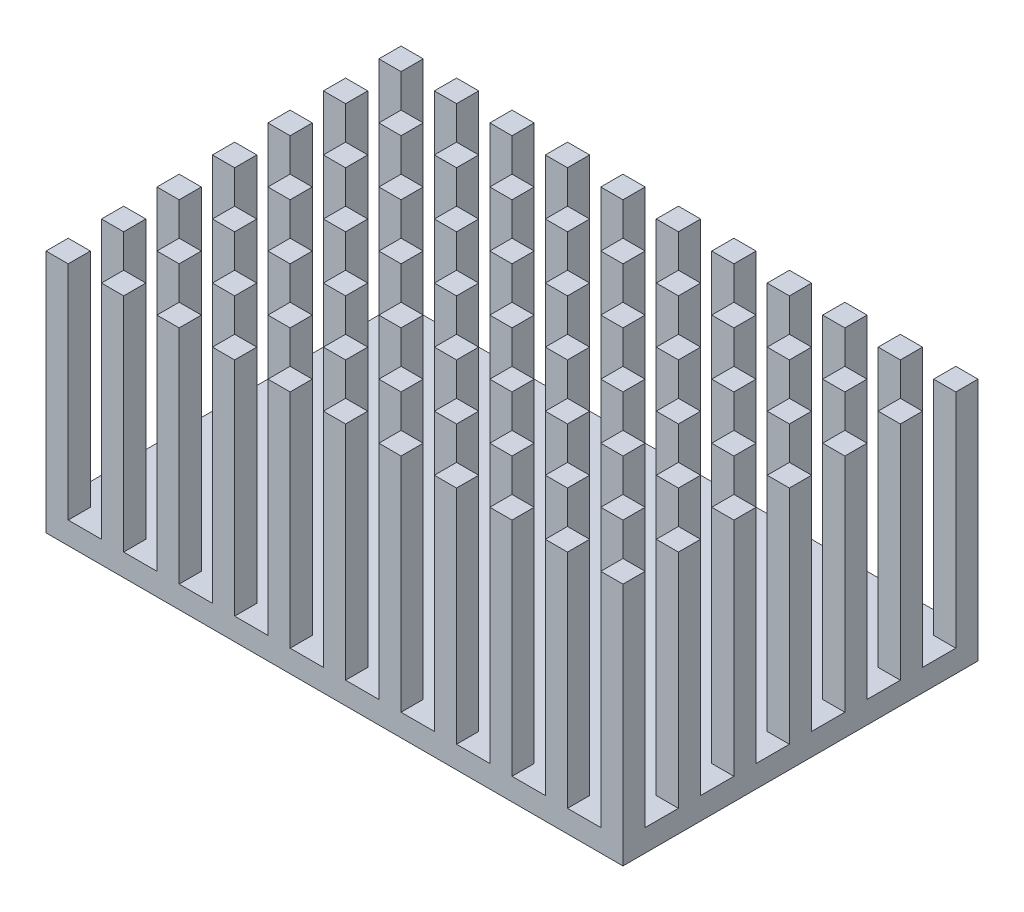
SolidWorks part; units mm, degrees
ref_plane "Front Plane" through (0, 0, 0) normal (0, 0, 1) x (1, 0, 0)
ref_plane "Top Plane" through (0, 0, 0) normal (0, 1, 0) x (1, 0, 0)
ref_plane "Right Plane" through (0, 0, 0) normal (1, 0, 0) x (0, 0, -1)
sketch "Sketch1" plane through (0, 0, 0) normal (0, 1, 0) x (1, 0, 0)
  line L1 (-26, 16) -> (26, 16)
  line L2 (-26, 16) -> (-26, -16)
  line L3 (-26, -16) -> (26, -16)
  line L4 (26, 16) -> (26, -16)
  line L5 (-26, 16) -> (26, -16) construction
  line L6 (-26, -16) -> (26, 16) construction
  point P0 (0, 0)
  dimension "D1" = 52
  dimension "D2" = 32
extrude "Boss-Extrude1" add sketch "Sketch1" along normal blind 2
sketch "Sketch2" plane through (0, 2, 0) normal (0, 1, 0) x (1, 0, 0)
  line L0 (-21, 16) -> (-19, 16)
  line L1 (-26, 16) -> (-24, 16)
  line L2 (-26, 16) -> (-26, 14)
  line L3 (-26, 14) -> (-24, 14)
  line L4 (-24, 16) -> (-24, 14)
  line L5 (-21, 16) -> (-21, 14)
  line L6 (-21, 14) -> (-19, 14)
  line L7 (-19, 16) -> (-19, 14)
  line L8 (-16, 16) -> (-14, 16)
  line L9 (-16, 16) -> (-16, 14)
  line L10 (-16, 14) -> (-14, 14)
  line L11 (-14, 16) -> (-14, 14)
  line L12 (-11, 16) -> (-9, 16)
  line L13 (-11, 16) -> (-11, 14)
  line L14 (-11, 14) -> (-9, 14)
  line L15 (-9, 16) -> (-9, 14)
  line L16 (-6, 16) -> (-4, 16)
  line L17 (-6, 16) -> (-6, 14)
  line L18 (-6, 14) -> (-4, 14)
  line L19 (-4, 16) -> (-4, 14)
  line L20 (-1, 16) -> (1, 16)
  line L21 (-1, 16) -> (-1, 14)
  line L22 (-1, 14) -> (1, 14)
  line L23 (1, 16) -> (1, 14)
  line L24 (4, 16) -> (6, 16)
  line L25 (4, 16) -> (4, 14)
  line L26 (4, 14) -> (6, 14)
  line L27 (6, 16) -> (6, 14)
  line L28 (9, 16) -> (11, 16)
  line L29 (9, 16) -> (9, 14)
  line L30 (9, 14) -> (11, 14)
  line L31 (11, 16) -> (11, 14)
  line L32 (14, 16) -> (16, 16)
  line L33 (14, 16) -> (14, 14)
  line L34 (14, 14) -> (16, 14)
  line L35 (16, 16) -> (16, 14)
  line L36 (19, 16) -> (21, 16)
  line L37 (19, 16) -> (19, 14)
  line L38 (19, 14) -> (21, 14)
  line L39 (21, 16) -> (21, 14)
  line L40 (24, 16) -> (26, 16)
  line L41 (24, 16) -> (24, 14)
  line L42 (24, 14) -> (26, 14)
  line L43 (26, 16) -> (26, 14)
  line L44 (-21, 11) -> (-19, 11)
  line L45 (-21, 11) -> (-21, 9)
  line L46 (-21, 9) -> (-19, 9)
  line L47 (-19, 11) -> (-19, 9)
  line L48 (-16, 11) -> (-14, 11)
  line L49 (-16, 11) -> (-16, 9)
  line L50 (-16, 9) -> (-14, 9)
  line L51 (-14, 11) -> (-14, 9)
  line L52 (-11, 11) -> (-9, 11)
  line L53 (-11, 11) -> (-11, 9)
  line L54 (-11, 9) -> (-9, 9)
  line L55 (-9, 11) -> (-9, 9)
  line L56 (-6, 11) -> (-4, 11)
  line L57 (-6, 11) -> (-6, 9)
  line L58 (-6, 9) -> (-4, 9)
  line L59 (-4, 11) -> (-4, 9)
  line L60 (-1, 11) -> (1, 11)
  line L61 (-1, 11) -> (-1, 9)
  line L62 (-1, 9) -> (1, 9)
  line L63 (1, 11) -> (1, 9)
  line L64 (4, 11) -> (6, 11)
  line L65 (4, 11) -> (4, 9)
  line L66 (4, 9) -> (6, 9)
  line L67 (6, 11) -> (6, 9)
  line L68 (9, 11) -> (11, 11)
  line L69 (9, 11) -> (9, 9)
  line L70 (9, 9) -> (11, 9)
  line L71 (11, 11) -> (11, 9)
  line L72 (14, 11) -> (16, 11)
  line L73 (14, 11) -> (14, 9)
  line L74 (14, 9) -> (16, 9)
  line L75 (16, 11) -> (16, 9)
  line L76 (19, 11) -> (21, 11)
  line L77 (19, 11) -> (19, 9)
  line L78 (19, 9) -> (21, 9)
  line L79 (21, 11) -> (21, 9)
  line L80 (24, 11) -> (26, 11)
  line L81 (24, 11) -> (24, 9)
  line L82 (24, 9) -> (26, 9)
  line L83 (26, 11) -> (26, 9)
  line L84 (-21, 6) -> (-19, 6)
  line L85 (-21, 6) -> (-21, 4)
  line L86 (-21, 4) -> (-19, 4)
  line L87 (-19, 6) -> (-19, 4)
  line L88 (-16, 6) -> (-14, 6)
  line L89 (-16, 6) -> (-16, 4)
  line L90 (-16, 4) -> (-14, 4)
  line L91 (-14, 6) -> (-14, 4)
  line L92 (-11, 6) -> (-9, 6)
  line L93 (-11, 6) -> (-11, 4)
  line L94 (-11, 4) -> (-9, 4)
  line L95 (-9, 6) -> (-9, 4)
  line L96 (-6, 6) -> (-4, 6)
  line L97 (-6, 6) -> (-6, 4)
  line L98 (-6, 4) -> (-4, 4)
  line L99 (-4, 6) -> (-4, 4)
  line L100 (-1, 6) -> (1, 6)
  line L101 (-1, 6) -> (-1, 4)
  line L102 (-1, 4) -> (1, 4)
  line L103 (1, 6) -> (1, 4)
  line L104 (4, 6) -> (6, 6)
  line L105 (4, 6) -> (4, 4)
  line L106 (4, 4) -> (6, 4)
  line L107 (6, 6) -> (6, 4)
  line L108 (9, 6) -> (11, 6)
  line L109 (9, 6) -> (9, 4)
  line L110 (9, 4) -> (11, 4)
  line L111 (11, 6) -> (11, 4)
  line L112 (14, 6) -> (16, 6)
  line L113 (14, 6) -> (14, 4)
  line L114 (14, 4) -> (16, 4)
  line L115 (16, 6) -> (16, 4)
  line L116 (19, 6) -> (21, 6)
  line L117 (19, 6) -> (19, 4)
  line L118 (19, 4) -> (21, 4)
  line L119 (21, 6) -> (21, 4)
  line L120 (24, 6) -> (26, 6)
  line L121 (24, 6) -> (24, 4)
  line L122 (24, 4) -> (26, 4)
  line L123 (26, 6) -> (26, 4)
  line L124 (-21, 1) -> (-19, 1)
  line L125 (-21, 1) -> (-21, -1)
  line L126 (-21, -1) -> (-19, -1)
  line L127 (-19, 1) -> (-19, -1)
  line L128 (-16, 1) -> (-14, 1)
  line L129 (-16, 1) -> (-16, -1)
  line L130 (-16, -1) -> (-14, -1)
  line L131 (-14, 1) -> (-14, -1)
  line L132 (-11, 1) -> (-9, 1)
  line L133 (-11, 1) -> (-11, -1)
  line L134 (-11, -1) -> (-9, -1)
  line L135 (-9, 1) -> (-9, -1)
  line L136 (-6, 1) -> (-4, 1)
  line L137 (-6, 1) -> (-6, -1)
  line L138 (-6, -1) -> (-4, -1)
  line L139 (-4, 1) -> (-4, -1)
  line L140 (-1, 1) -> (1, 1)
  line L141 (-1, 1) -> (-1, -1)
  line L142 (-1, -1) -> (1, -1)
  line L143 (1, 1) -> (1, -1)
  line L144 (4, 1) -> (6, 1)
  line L145 (4, 1) -> (4, -1)
  line L146 (4, -1) -> (6, -1)
  line L147 (6, 1) -> (6, -1)
  line L148 (9, 1) -> (11, 1)
  line L149 (9, 1) -> (9, -1)
  line L150 (9, -1) -> (11, -1)
  line L151 (11, 1) -> (11, -1)
  line L152 (14, 1) -> (16, 1)
  line L153 (14, 1) -> (14, -1)
  line L154 (14, -1) -> (16, -1)
  line L155 (16, 1) -> (16, -1)
  line L156 (19, 1) -> (21, 1)
  line L157 (19, 1) -> (19, -1)
  line L158 (19, -1) -> (21, -1)
  line L159 (21, 1) -> (21, -1)
  line L160 (24, 1) -> (26, 1)
  line L161 (24, 1) -> (24, -1)
  line L162 (24, -1) -> (26, -1)
  line L163 (26, 1) -> (26, -1)
  line L164 (-21, -4) -> (-19, -4)
  line L165 (-21, -4) -> (-21, -6)
  line L166 (-21, -6) -> (-19, -6)
  line L167 (-19, -4) -> (-19, -6)
  line L168 (-16, -4) -> (-14, -4)
  line L169 (-16, -4) -> (-16, -6)
  line L170 (-16, -6) -> (-14, -6)
  line L171 (-14, -4) -> (-14, -6)
  line L172 (-11, -4) -> (-9, -4)
  line L173 (-11, -4) -> (-11, -6)
  line L174 (-11, -6) -> (-9, -6)
  line L175 (-9, -4) -> (-9, -6)
  line L176 (-6, -4) -> (-4, -4)
  line L177 (-6, -4) -> (-6, -6)
  line L178 (-6, -6) -> (-4, -6)
  line L179 (-4, -4) -> (-4, -6)
  line L180 (-1, -4) -> (1, -4)
  line L181 (-1, -4) -> (-1, -6)
  line L182 (-1, -6) -> (1, -6)
  line L183 (1, -4) -> (1, -6)
  line L184 (4, -4) -> (6, -4)
  line L185 (4, -4) -> (4, -6)
  line L186 (4, -6) -> (6, -6)
  line L187 (6, -4) -> (6, -6)
  line L188 (9, -4) -> (11, -4)
  line L189 (9, -4) -> (9, -6)
  line L190 (9, -6) -> (11, -6)
  line L191 (11, -4) -> (11, -6)
  line L192 (14, -4) -> (16, -4)
  line L193 (14, -4) -> (14, -6)
  line L194 (14, -6) -> (16, -6)
  line L195 (16, -4) -> (16, -6)
  line L196 (19, -4) -> (21, -4)
  line L197 (19, -4) -> (19, -6)
  line L198 (19, -6) -> (21, -6)
  line L199 (21, -4) -> (21, -6)
  line L200 (24, -4) -> (26, -4)
  line L201 (24, -4) -> (24, -6)
  line L202 (24, -6) -> (26, -6)
  line L203 (26, -4) -> (26, -6)
  line L204 (-21, -9) -> (-19, -9)
  line L205 (-21, -9) -> (-21, -11)
  line L206 (-21, -11) -> (-19, -11)
  line L207 (-19, -9) -> (-19, -11)
  line L208 (-16, -9) -> (-14, -9)
  line L209 (-16, -9) -> (-16, -11)
  line L210 (-16, -11) -> (-14, -11)
  line L211 (-14, -9) -> (-14, -11)
  line L212 (-11, -9) -> (-9, -9)
  line L213 (-11, -9) -> (-11, -11)
  line L214 (-11, -11) -> (-9, -11)
  line L215 (-9, -9) -> (-9, -11)
  line L216 (-6, -9) -> (-4, -9)
  line L217 (-6, -9) -> (-6, -11)
  line L218 (-6, -11) -> (-4, -11)
  line L219 (-4, -9) -> (-4, -11)
  line L220 (-1, -9) -> (1, -9)
  line L221 (-1, -9) -> (-1, -11)
  line L222 (-1, -11) -> (1, -11)
  line L223 (1, -9) -> (1, -11)
  line L224 (4, -9) -> (6, -9)
  line L225 (4, -9) -> (4, -11)
  line L226 (4, -11) -> (6, -11)
  line L227 (6, -9) -> (6, -11)
  line L228 (9, -9) -> (11, -9)
  line L229 (9, -9) -> (9, -11)
  line L230 (9, -11) -> (11, -11)
  line L231 (11, -9) -> (11, -11)
  line L232 (14, -9) -> (16, -9)
  line L233 (14, -9) -> (14, -11)
  line L234 (14, -11) -> (16, -11)
  line L235 (16, -9) -> (16, -11)
  line L236 (19, -9) -> (21, -9)
  line L237 (19, -9) -> (19, -11)
  line L238 (19, -11) -> (21, -11)
  line L239 (21, -9) -> (21, -11)
  line L240 (24, -9) -> (26, -9)
  line L241 (24, -9) -> (24, -11)
  line L242 (24, -11) -> (26, -11)
  line L243 (26, -9) -> (26, -11)
  line L244 (-21, -14) -> (-19, -14)
  line L245 (-21, -14) -> (-21, -16)
  line L246 (-21, -16) -> (-19, -16)
  line L247 (-19, -14) -> (-19, -16)
  line L248 (-16, -14) -> (-14, -14)
  line L249 (-16, -14) -> (-16, -16)
  line L250 (-16, -16) -> (-14, -16)
  line L251 (-14, -14) -> (-14, -16)
  line L252 (-11, -14) -> (-9, -14)
  line L253 (-11, -14) -> (-11, -16)
  line L254 (-11, -16) -> (-9, -16)
  line L255 (-9, -14) -> (-9, -16)
  line L256 (-6, -14) -> (-4, -14)
  line L257 (-6, -14) -> (-6, -16)
  line L258 (-6, -16) -> (-4, -16)
  line L259 (-4, -14) -> (-4, -16)
  line L260 (-1, -14) -> (1, -14)
  line L261 (-1, -14) -> (-1, -16)
  line L262 (-1, -16) -> (1, -16)
  line L263 (1, -14) -> (1, -16)
  line L264 (4, -14) -> (6, -14)
  line L265 (4, -14) -> (4, -16)
  line L266 (4, -16) -> (6, -16)
  line L267 (6, -14) -> (6, -16)
  line L268 (9, -14) -> (11, -14)
  line L269 (9, -14) -> (9, -16)
  line L270 (9, -16) -> (11, -16)
  line L271 (11, -14) -> (11, -16)
  line L272 (14, -14) -> (16, -14)
  line L273 (14, -14) -> (14, -16)
  line L274 (14, -16) -> (16, -16)
  line L275 (16, -14) -> (16, -16)
  line L276 (19, -14) -> (21, -14)
  line L277 (19, -14) -> (19, -16)
  line L278 (19, -16) -> (21, -16)
  line L279 (21, -14) -> (21, -16)
  line L280 (24, -14) -> (26, -14)
  line L281 (24, -14) -> (24, -16)
  line L282 (24, -16) -> (26, -16)
  line L283 (26, -14) -> (26, -16)
  line L284 (-26, 11) -> (-24, 11)
  line L285 (-26, 11) -> (-26, 9)
  line L286 (-26, 9) -> (-24, 9)
  line L287 (-24, 11) -> (-24, 9)
  line L288 (-26, 6) -> (-24, 6)
  line L289 (-26, 6) -> (-26, 4)
  line L290 (-26, 4) -> (-24, 4)
  line L291 (-24, 6) -> (-24, 4)
  line L292 (-26, 1) -> (-24, 1)
  line L293 (-26, 1) -> (-26, -1)
  line L294 (-26, -1) -> (-24, -1)
  line L295 (-24, 1) -> (-24, -1)
  line L296 (-26, -4) -> (-24, -4)
  line L297 (-26, -4) -> (-26, -6)
  line L298 (-26, -6) -> (-24, -6)
  line L299 (-24, -4) -> (-24, -6)
  line L300 (-26, -9) -> (-24, -9)
  line L301 (-26, -9) -> (-26, -11)
  line L302 (-26, -11) -> (-24, -11)
  line L303 (-24, -9) -> (-24, -11)
  line L304 (-26, -14) -> (-24, -14)
  line L305 (-26, -14) -> (-26, -16)
  line L306 (-26, -16) -> (-24, -16)
  line L307 (-24, -14) -> (-24, -16)
  dimension "D1" = 2
  dimension "D2" = 2
  dimension "D3" = 11
  dimension "D4" = 7
extrude "Boss-Extrude2" add sketch "Sketch2" along normal blind 20
